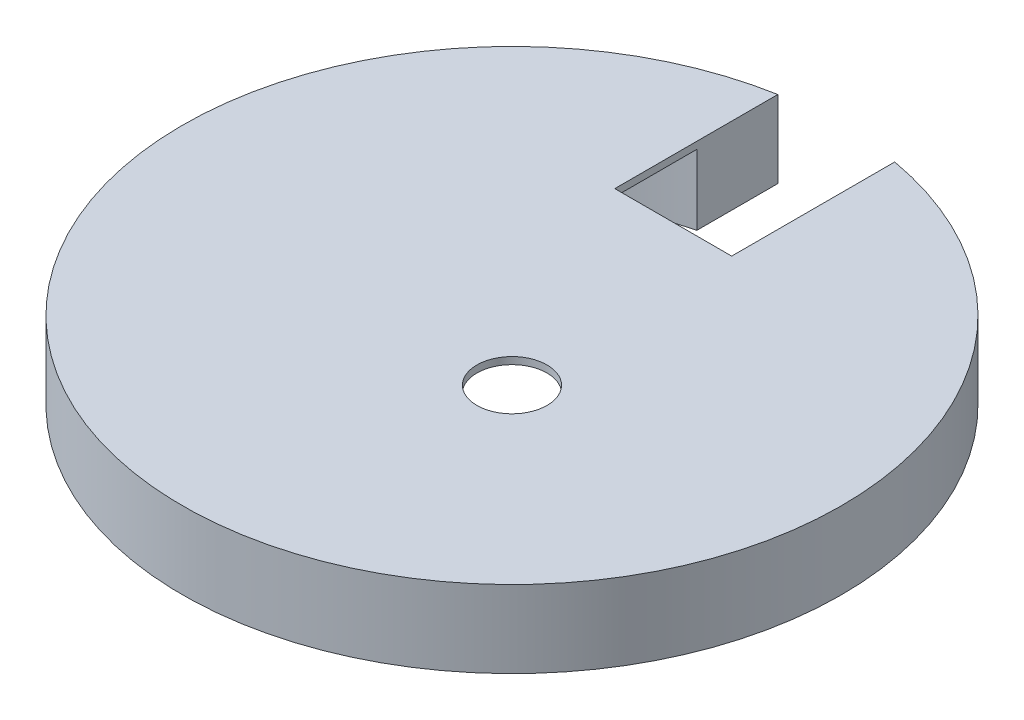
SolidWorks part; units mm, degrees
material "PBT General Purpose"
ref_plane "Front Plane" through (0, 0, 0) normal (0, 0, 1) x (1, 0, 0)
ref_plane "Top Plane" through (0, 0, 0) normal (0, 1, 0) x (1, 0, 0)
ref_plane "Right Plane" through (0, 0, 0) normal (1, 0, 0) x (0, 0, -1)
sketch "Sketch2" plane through (0, 0, 0) normal (0, 1, 0) x (1, 0, 0)
  line L0 (-8.33, 46.2254) -> (-8.33, 34.6855)
  line L2 (8.33, 34.6855) -> (8.33, 46.2254)
  circle A0 centre (0, 0) radius 46.97 construction
  arc A1 (-8.33, 46.2254) -> (8.33, 46.2254) centre (0, 0) ccw
  circle A2 centre (0, 0) radius 35.6718 construction
  arc A4 (-8.33, 34.6855) -> (8.33, 34.6855) centre (0, 0) ccw
  point P5 (-8.33, 34.6918)
  point P9 (0, 0)
  dimension "D1" = 93.94
  dimension "D4" = 71.3435
  dimension "D2" = 16.66
extrude "Boss-Extrude1" add sketch "Sketch2" along normal blind 10
sketch "Sketch3" plane through (0, 10, 0) normal (0, 1, 0) x (1, 0, 0)
  line L0 (8.33, 46.2254) -> (8.33, 34.6855) construction
  line L1 (-8.33, 46.2254) -> (-8.33, 22.9854)
  line L2 (-8.33, 22.9854) -> (8.33, 22.9854)
  line L3 (8.33, 22.9854) -> (8.33, 46.2254)
  circle A0 centre (0, 0) radius 46.97 construction
  arc A1 (-8.33, 46.2254) -> (8.33, 46.2254) centre (0, 0) ccw construction
  arc A2 (-8.33, 46.2254) -> (8.33, 46.2254) centre (0, 0) ccw
  dimension "D1" = 23.24
extrude "Boss-Extrude2" add sketch "Sketch3" along normal blind 1
sketch "Sketch4" plane through (0, 11, 0) normal (0, 1, 0) x (1, 0, 0)
  line L0 (0, 0) -> (8.6055, -8.6055) construction
  line L1 (0, 0) -> (0, -46.97) construction
  circle A0 centre (8.6055, -8.6055) radius 5
  arc A1 (-8.33, 46.2254) -> (8.33, 46.2254) centre (0, 0) ccw construction
  dimension "D3" = 10
  dimension "D1" = 12.17
  dimension "D2" = 45
extrude "Cut-Extrude1" cut sketch "Sketch4" against normal through all
sketch "Logo Sketch" plane through (0, 11, 0) normal (0, 1, 0) x (1, 0, 0)
  line L0 (-29.1725, 7.5003) -> (-43.8748, 7.5003) construction
  text T0 "RoboSharks" font "BankGothic Md BT" height 5
  point P3 (-27.6875, -7.9088)
  point P4 (0, 0)
  point P5 (-23.0177, -1.9256)
  point P6 (-43.5942, -2.2175)
  point P7 (-36.0057, -2.2175)
  point P8 (-16.1589, 3.7657)
  point P9 (0, 0)
  point P10 (0, 0)
  point P11 (-22.7258, 4.6413)
